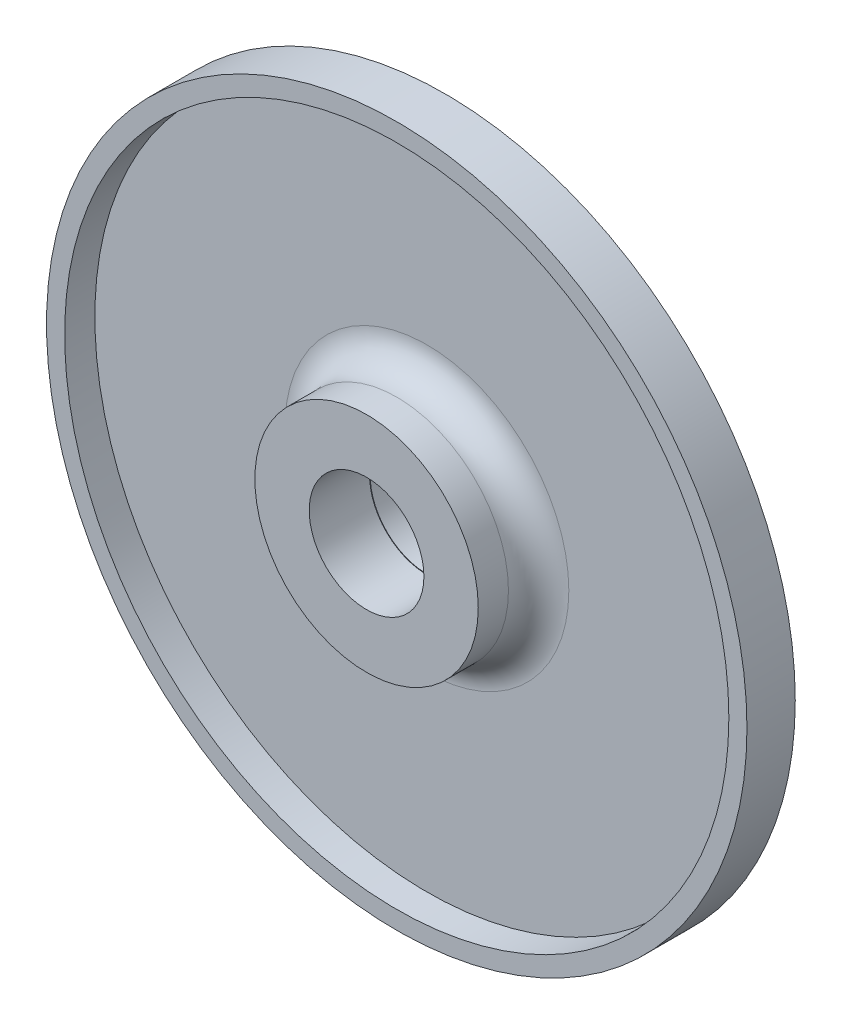
SolidWorks part; units mm, degrees
material "Cast Alloy Steel"
ref_plane "Front Plane" through (0, 0, 0) normal (0, 0, 1) x (1, 0, 0)
ref_plane "Top Plane" through (0, 0, 0) normal (0, 1, 0) x (1, 0, 0)
ref_plane "Right Plane" through (0, 0, 0) normal (1, 0, 0) x (0, 0, -1)
sketch "Sketch1" plane through (0, 0, 0) normal (0, 0, 1) x (1, 0, 0)
  circle A0 centre (0, 0) radius 58
extrude "Boss-Extrude1" add sketch "Sketch1" along normal blind 8
sketch "Sketch2" plane through (0, 0, 8) normal (0, 0, 1) x (1, 0, 0)
  circle A0 centre (0, 0) radius 55
extrude "Cut-Extrude1" cut sketch "Sketch2" against normal blind 5
sketch "Sketch3" plane through (0, 0, 3) normal (0, 0, 1) x (1, 0, 0)
  circle A0 centre (0, 0) radius 18.5
  circle A1 centre (0, 0) radius 9.5
extrude "Boss-Extrude2" add sketch "Sketch3" along normal blind 10
fillet "Fillet1" radius 5 1 edges at (18.5, 0, 3)
sketch "Sketch4" plane through (0, 0, 0) normal (0, 0, -1) x (-1, 0, 0)
  circle A0 centre (0, 0) radius 9.4
  circle A1 centre (0, 0) radius 13.315
extrude "Boss-Extrude3" add sketch "Sketch4" along normal blind 17
sketch "Sketch5" plane through (0, 0, 0) normal (0, 0, -1) x (-1, 0, 0)
  circle A0 centre (0, 0) radius 9.4
extrude "Cut-Extrude2" cut sketch "Sketch5" against normal blind 17
